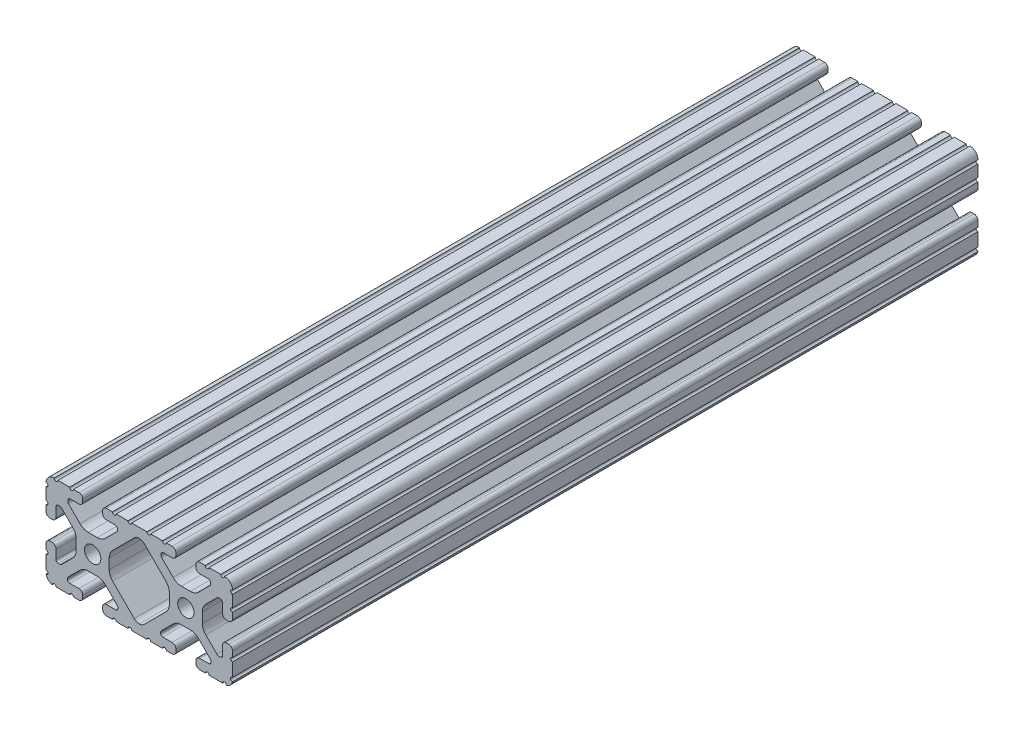
SolidWorks part; units mm, degrees
material "6005A-T61"
ref_plane "Front Plane" through (0, 0, 0) normal (0, 0, 1) x (1, 0, 0)
ref_plane "Top Plane" through (0, 0, 0) normal (0, 1, 0) x (1, 0, 0)
ref_plane "Right Plane" through (0, 0, 0) normal (1, 0, 0) x (0, 0, -1)
sketch "Sketch1" plane through (0, 0, 0) normal (0, 0, 1) x (1, 0, 0)
  line L0 (-3.1211, -19.05) -> (3.1211, -19.05)
  line L1 (-38.1, 10.287) -> (-38.1, 14.3752)
  line L2 (0, -34.5561) -> (0, 32.8014) construction
  line L3 (-38.1, 0) -> (0, 0) construction
  line L4 (-38.1, 9.5497) -> (-38.1, 10.287)
  line L5 (-19.05, 19.05) -> (-19.05, -20.2827) construction
  line L6 (0, -15.1247) -> (0, -15.1131) construction
  line L7 (9.1761, 12.9058) -> (13.8525, 8.2294)
  line L8 (8.9158, 14.097) -> (8.9158, 13.5344)
  line L9 (13.4112, 14.986) -> (9.8048, 14.986)
  line L10 (14.986, 17.4968) -> (14.986, 16.5608)
  line L11 (10.9975, 19.05) -> (13.4328, 19.05)
  line L12 (8.6331, 19.05) -> (9.4735, 19.05)
  line L13 (4.6451, 19.05) -> (8.6331, 19.05)
  line L14 (31.792, 10.0266) -> (27.1976, 5.4321)
  line L15 (33.147, 10.287) -> (32.4207, 10.287)
  line L16 (29.2071, 19.05) -> (33.2963, 19.05)
  line L17 (28.4698, 19.05) -> (29.2071, 19.05)
  line L18 (-38.1, 5.6388) -> (-38.1, 8.0257)
  line L19 (24.5589, 19.05) -> (26.9458, 19.05)
  line L20 (23.114, 16.5608) -> (23.114, 17.4806)
  line L21 (28.2952, 14.986) -> (24.6888, 14.986)
  line L22 (29.1842, 13.5344) -> (29.1842, 14.097)
  line L23 (-34.036, 9.398) -> (-34.036, 5.6388)
  line L24 (-35.6108, 4.064) -> (-36.5252, 4.064)
  line L25 (24.2475, 8.2294) -> (28.9239, 12.9058)
  line L26 (25.8064, -2.0735) -> (25.8064, 2.0735)
  line L27 (35.6108, 4.064) -> (36.5252, 4.064)
  line L28 (34.036, 9.398) -> (34.036, 5.6388)
  line L29 (38.1, 5.6388) -> (38.1, 8.0257)
  line L30 (38.1, 9.5497) -> (38.1, 10.287)
  line L31 (38.1, 10.287) -> (38.1, 14.3752)
  line L32 (17.2111, 6.8382) -> (20.8889, 6.8382)
  line L33 (2.077, 14.2576) -> (10.9024, 5.4321)
  line L34 (-31.792, -10.0266) -> (-27.1976, -5.4321)
  line L35 (-33.147, -10.287) -> (-32.4207, -10.287)
  line L36 (-29.2071, -19.05) -> (-34.0473, -19.05)
  line L37 (-28.4698, -19.05) -> (-29.2071, -19.05)
  line L38 (-24.6888, -19.05) -> (-26.9458, -19.05)
  line L39 (12.2936, -2.0735) -> (12.2936, 2.0735)
  line L40 (-23.114, -16.5608) -> (-23.114, -17.4752)
  line L41 (-28.448, -14.986) -> (-24.6888, -14.986)
  line L42 (-29.337, -13.6872) -> (-29.337, -14.097)
  line L43 (2.077, -14.2576) -> (10.9024, -5.4321)
  line L44 (-3.1211, 19.05) -> (3.1211, 19.05)
  line L45 (8.763, -14.097) -> (8.763, -13.6872)
  line L46 (-24.2475, -8.2294) -> (-29.0766, -13.0586)
  line L47 (-35.6108, -4.064) -> (-36.5252, -4.064)
  line L48 (-34.036, -9.398) -> (-34.036, -5.6388)
  line L49 (-38.1, -5.6388) -> (-38.1, -8.0257)
  line L50 (-38.1, -9.5497) -> (-38.1, -10.287)
  line L51 (-38.1, -10.287) -> (-38.1, -15.036)
  line L52 (17.2111, -6.8382) -> (20.8889, -6.8382)
  line L53 (38.1, -10.287) -> (38.1, -15.036)
  line L54 (38.1, -9.5497) -> (38.1, -10.287)
  line L55 (38.1, -5.6388) -> (38.1, -8.0257)
  line L56 (34.036, -9.398) -> (34.036, -5.6388)
  line L57 (35.6108, -4.064) -> (36.5252, -4.064)
  line L58 (24.2475, -8.2294) -> (29.0766, -13.0586)
  line L59 (29.337, -13.6872) -> (29.337, -14.097)
  line L60 (-17.2111, -6.8382) -> (-20.8889, -6.8382)
  line L61 (-9.0234, -13.0586) -> (-13.8525, -8.2294)
  line L62 (-8.763, -14.097) -> (-8.763, -13.6872)
  line L63 (-13.4112, -14.986) -> (-9.652, -14.986)
  line L64 (-14.986, -17.4752) -> (-14.986, -16.5608)
  line L65 (-10.9975, -19.05) -> (-13.4112, -19.05)
  line L66 (28.448, -14.986) -> (24.6888, -14.986)
  line L67 (23.114, -16.5608) -> (23.114, -17.4752)
  line L68 (24.6888, -19.05) -> (26.9458, -19.05)
  line L69 (28.4698, -19.05) -> (29.2071, -19.05)
  line L70 (29.2071, -19.05) -> (34.0473, -19.05)
  line L71 (-8.6331, -19.05) -> (-9.4735, -19.05)
  line L72 (33.147, -10.287) -> (32.4207, -10.287)
  line L73 (31.792, -10.0266) -> (27.1976, -5.4321)
  line L74 (-4.6451, -19.05) -> (-8.6331, -19.05)
  line L75 (9.0234, -13.0586) -> (13.8525, -8.2294)
  line L76 (13.4112, -14.986) -> (9.652, -14.986)
  line L77 (-2.077, -14.2576) -> (-10.9024, -5.4321)
  line L78 (14.986, -17.4752) -> (14.986, -16.5608)
  line L79 (10.9975, -19.05) -> (13.4112, -19.05)
  line L80 (4.6451, -19.05) -> (8.6331, -19.05)
  line L81 (8.6331, -19.05) -> (9.4735, -19.05)
  line L83 (-12.2936, -2.0735) -> (-12.2936, 2.0735)
  line L84 (-25.8064, -2.0735) -> (-25.8064, 2.0735)
  line L85 (-2.077, 14.2576) -> (-10.9024, 5.4321)
  line L87 (-4.6451, 19.05) -> (-8.6331, 19.05)
  line L88 (-8.6331, 19.05) -> (-9.4735, 19.05)
  line L89 (-10.9975, 19.05) -> (-13.4328, 19.05)
  line L90 (-14.986, 17.4968) -> (-14.986, 16.5608)
  line L91 (-13.4112, 14.986) -> (-9.8048, 14.986)
  line L92 (-8.9158, 14.097) -> (-8.9158, 13.5344)
  line L93 (-9.1761, 12.9058) -> (-13.8525, 8.2294)
  line L94 (-17.2111, 6.8382) -> (-20.8889, 6.8382)
  line L95 (-24.2475, 8.2294) -> (-28.9239, 12.9058)
  line L96 (-29.1842, 13.5344) -> (-29.1842, 14.097)
  line L97 (-28.2952, 14.986) -> (-24.6888, 14.986)
  line L98 (-23.114, 16.5608) -> (-23.114, 17.4806)
  line L99 (-24.5589, 19.05) -> (-26.9458, 19.05)
  line L100 (-28.4698, 19.05) -> (-29.2071, 19.05)
  line L101 (-29.2071, 19.05) -> (-33.2963, 19.05)
  line L109 (-33.147, 10.287) -> (-32.4207, 10.287)
  line L165 (-31.792, 10.0266) -> (-27.1976, 5.4321)
  arc A0 (-38.1376, 15.8983) -> (-38.1, 14.3752) centre (-38.1, 15.1372) cw
  arc A1 (-38.1, 9.5497) -> (-38.1, 8.0257) centre (-38.1, 8.7877) cw
  arc A2 (9.1761, 12.9058) -> (8.9158, 13.5344) centre (9.8048, 13.5344) cw
  arc A3 (8.9158, 14.097) -> (9.8048, 14.986) centre (9.8048, 14.097) cw
  arc A4 (-36.5252, 4.064) -> (-38.1, 5.6388) centre (-36.5252, 5.6388) cw
  arc A5 (14.986, 16.5608) -> (13.4112, 14.986) centre (13.4112, 16.5608) cw
  arc A6 (13.4328, 19.05) -> (14.986, 17.4968) centre (13.4328, 17.4968) cw
  arc A7 (10.9975, 19.05) -> (9.4735, 19.05) centre (10.2355, 19.05) cw
  arc A8 (4.6451, 19.05) -> (3.1211, 19.05) centre (3.8831, 19.05) cw
  arc A9 (0, 15.1131) -> (2.077, 14.2576) centre (0.0116, 12.1921) cw
  arc A10 (25.8064, 2.0735) -> (27.1976, 5.4321) centre (30.5562, 2.0735) cw
  arc A11 (31.792, 10.0266) -> (32.4207, 10.287) centre (32.4207, 9.398) cw
  arc A12 (33.147, 10.287) -> (34.036, 9.398) centre (33.147, 9.398) cw
  arc A13 (34.8195, 19.0968) -> (38.1376, 15.8983) centre (34.903, 15.8631) cw
  arc A14 (34.8195, 19.0968) -> (33.2963, 19.05) centre (34.0579, 19.0734) cw
  arc A15 (28.4698, 19.05) -> (26.9458, 19.05) centre (27.7078, 19.05) cw
  arc A16 (23.114, 17.4806) -> (24.5589, 19.05) centre (24.6888, 17.4806) cw
  arc A17 (24.6888, 14.986) -> (23.114, 16.5608) centre (24.6888, 16.5608) cw
  arc A18 (28.2952, 14.986) -> (29.1842, 14.097) centre (28.2952, 14.097) cw
  arc A19 (29.1842, 13.5344) -> (28.9239, 12.9058) centre (28.2952, 13.5344) cw
  arc A20 (-35.5713, -19.05) -> (-38.1, -16.56) centre (-34.9455, -15.8855) cw
  arc A21 (34.036, 5.6388) -> (35.6108, 4.064) centre (35.6108, 5.6388) ccw
  arc A22 (36.5252, 4.064) -> (38.1, 5.6388) centre (36.5252, 5.6388) ccw
  arc A23 (38.1, 9.5497) -> (38.1, 8.0257) centre (38.1, 8.7877) ccw
  arc A24 (24.2475, 8.2294) -> (20.8889, 6.8382) centre (20.8889, 11.588) cw
  arc A25 (17.2111, 6.8382) -> (13.8525, 8.2294) centre (17.2111, 11.588) cw
  arc A26 (10.9024, 5.4321) -> (12.2936, 2.0735) centre (7.5438, 2.0735) cw
  arc A27 (0, -15.1131) -> (2.077, -14.2576) centre (0.0116, -12.1921) ccw
  arc A28 (-34.036, 5.6388) -> (-35.6108, 4.064) centre (-35.6108, 5.6388) cw
  arc A29 (-25.8064, -2.0735) -> (-27.1976, -5.4321) centre (-30.5562, -2.0735) cw
  arc A30 (-31.792, -10.0266) -> (-32.4207, -10.287) centre (-32.4207, -9.398) cw
  arc A31 (-33.147, -10.287) -> (-34.036, -9.398) centre (-33.147, -9.398) cw
  arc A33 (-35.5713, -19.05) -> (-34.0473, -19.05) centre (-34.8093, -19.05) cw
  arc A34 (-28.4698, -19.05) -> (-26.9458, -19.05) centre (-27.7078, -19.05) cw
  arc A35 (10.9024, -5.4321) -> (12.2936, -2.0735) centre (7.5438, -2.0735) ccw
  circle A36 centre (19.05, 0) radius 3.3274
  arc A37 (-23.114, -17.4752) -> (-24.6888, -19.05) centre (-24.6888, -17.4752) cw
  arc A38 (-24.6888, -14.986) -> (-23.114, -16.5608) centre (-24.6888, -16.5608) cw
  arc A39 (-28.448, -14.986) -> (-29.337, -14.097) centre (-28.448, -14.097) cw
  arc A40 (-29.337, -13.6872) -> (-29.0766, -13.0586) centre (-28.448, -13.6872) cw
  arc A41 (-24.2475, -8.2294) -> (-20.8889, -6.8382) centre (-20.8889, -11.588) cw
  arc A42 (-34.036, -5.6388) -> (-35.6108, -4.064) centre (-35.6108, -5.6388) ccw
  arc A43 (-36.5252, -4.064) -> (-38.1, -5.6388) centre (-36.5252, -5.6388) ccw
  arc A44 (-38.1, -9.5497) -> (-38.1, -8.0257) centre (-38.1, -8.7877) ccw
  arc A45 (-38.1, -16.56) -> (-38.1, -15.036) centre (-38.1, -15.798) ccw
  arc A46 (38.1, -16.56) -> (38.1, -15.036) centre (38.1, -15.798) cw
  arc A47 (38.1, -9.5497) -> (38.1, -8.0257) centre (38.1, -8.7877) cw
  arc A48 (36.5252, -4.064) -> (38.1, -5.6388) centre (36.5252, -5.6388) cw
  arc A49 (34.036, -5.6388) -> (35.6108, -4.064) centre (35.6108, -5.6388) cw
  arc A50 (24.2475, -8.2294) -> (20.8889, -6.8382) centre (20.8889, -11.588) ccw
  arc A51 (29.337, -13.6872) -> (29.0766, -13.0586) centre (28.448, -13.6872) ccw
  arc A52 (28.448, -14.986) -> (29.337, -14.097) centre (28.448, -14.097) ccw
  arc A53 (24.6888, -14.986) -> (23.114, -16.5608) centre (24.6888, -16.5608) ccw
  arc A54 (-17.2111, -6.8382) -> (-13.8525, -8.2294) centre (-17.2111, -11.588) cw
  arc A55 (-9.0234, -13.0586) -> (-8.763, -13.6872) centre (-9.652, -13.6872) cw
  arc A56 (-8.763, -14.097) -> (-9.652, -14.986) centre (-9.652, -14.097) cw
  arc A57 (-14.986, -16.5608) -> (-13.4112, -14.986) centre (-13.4112, -16.5608) cw
  arc A58 (-13.4112, -19.05) -> (-14.986, -17.4752) centre (-13.4112, -17.4752) cw
  arc A59 (-10.9975, -19.05) -> (-9.4735, -19.05) centre (-10.2355, -19.05) cw
  arc A60 (-4.6451, -19.05) -> (-3.1211, -19.05) centre (-3.8831, -19.05) cw
  arc A61 (23.114, -17.4752) -> (24.6888, -19.05) centre (24.6888, -17.4752) ccw
  arc A62 (28.4698, -19.05) -> (26.9458, -19.05) centre (27.7078, -19.05) ccw
  arc A63 (35.5713, -19.05) -> (34.0473, -19.05) centre (34.8093, -19.05) ccw
  arc A64 (35.5713, -19.05) -> (38.1, -16.56) centre (34.9379, -15.8778) ccw
  arc A65 (33.147, -10.287) -> (34.036, -9.398) centre (33.147, -9.398) ccw
  arc A66 (31.792, -10.0266) -> (32.4207, -10.287) centre (32.4207, -9.398) ccw
  arc A67 (-10.9024, -5.4321) -> (-12.2936, -2.0735) centre (-7.5438, -2.0735) cw
  arc A68 (0, -15.1131) -> (-2.077, -14.2576) centre (-0.0116, -12.1921) cw
  arc A69 (0, 15.1131) -> (-2.077, 14.2576) centre (-0.0116, 12.1921) ccw
  arc A70 (-10.9024, 5.4321) -> (-12.2936, 2.0735) centre (-7.5438, 2.0735) ccw
  arc A71 (25.8064, -2.0735) -> (27.1976, -5.4321) centre (30.5562, -2.0735) ccw
  arc A72 (9.0234, -13.0586) -> (8.763, -13.6872) centre (9.652, -13.6872) ccw
  arc A73 (8.763, -14.097) -> (9.652, -14.986) centre (9.652, -14.097) ccw
  arc A74 (17.2111, -6.8382) -> (13.8525, -8.2294) centre (17.2111, -11.588) ccw
  arc A75 (13.4112, -19.05) -> (14.986, -17.4752) centre (13.4112, -17.4752) ccw
  arc A76 (14.986, -16.5608) -> (13.4112, -14.986) centre (13.4112, -16.5608) ccw
  arc A77 (-4.6451, 19.05) -> (-3.1211, 19.05) centre (-3.8831, 19.05) ccw
  arc A78 (-10.9975, 19.05) -> (-9.4735, 19.05) centre (-10.2355, 19.05) ccw
  arc A79 (-13.4328, 19.05) -> (-14.986, 17.4968) centre (-13.4328, 17.4968) ccw
  arc A80 (-14.986, 16.5608) -> (-13.4112, 14.986) centre (-13.4112, 16.5608) ccw
  arc A81 (-8.9158, 14.097) -> (-9.8048, 14.986) centre (-9.8048, 14.097) ccw
  arc A82 (-9.1761, 12.9058) -> (-8.9158, 13.5344) centre (-9.8048, 13.5344) ccw
  arc A83 (-17.2111, 6.8382) -> (-13.8525, 8.2294) centre (-17.2111, 11.588) ccw
  arc A84 (-24.2475, 8.2294) -> (-20.8889, 6.8382) centre (-20.8889, 11.588) ccw
  arc A85 (-29.1842, 13.5344) -> (-28.9239, 12.9058) centre (-28.2952, 13.5344) ccw
  arc A86 (-28.2952, 14.986) -> (-29.1842, 14.097) centre (-28.2952, 14.097) ccw
  arc A87 (-24.6888, 14.986) -> (-23.114, 16.5608) centre (-24.6888, 16.5608) ccw
  arc A88 (-23.114, 17.4806) -> (-24.5589, 19.05) centre (-24.6888, 17.4806) ccw
  arc A89 (-28.4698, 19.05) -> (-26.9458, 19.05) centre (-27.7078, 19.05) ccw
  arc A90 (-34.8195, 19.0968) -> (-33.2963, 19.05) centre (-34.0579, 19.0734) ccw
  arc A91 (-34.8195, 19.0968) -> (-38.1376, 15.8983) centre (-34.903, 15.8631) ccw
  arc A92 (4.6451, -19.05) -> (3.1211, -19.05) centre (3.8831, -19.05) ccw
  arc A93 (10.9975, -19.05) -> (9.4735, -19.05) centre (10.2355, -19.05) ccw
  arc A94 (38.1376, 15.8983) -> (38.1, 14.3752) centre (38.1, 15.1372) ccw
  arc A96 (-33.147, 10.287) -> (-34.036, 9.398) centre (-33.147, 9.398) ccw
  arc A97 (-31.792, 10.0266) -> (-32.4207, 10.287) centre (-32.4207, 9.398) ccw
  arc A98 (-25.8064, 2.0735) -> (-27.1976, 5.4321) centre (-30.5562, 2.0735) ccw
  circle A101 centre (-19.05, 0) radius 3.3274
  point P34 (0, 19.05)
  point P79 (25.6765, 0)
  point P274 (0, -19.05)
  point P282 (-25.6765, 0)
  point P283 (-12.2936, 0)
  dimension "D1" = 38.1
  dimension "D4" = 6.6548
  dimension "D10" = 4.064
  dimension "D2" = 76.2
  dimension "D3" = 38.1
  dimension "D5" = 8.128
  dimension "D6" = 20.574
  dimension "D7" = 12.2936
  dimension "D8" = 4.064
  dimension "D9" = 4.064
extrude "Extrude1" add sketch "Sketch1" against normal blind 304.8
